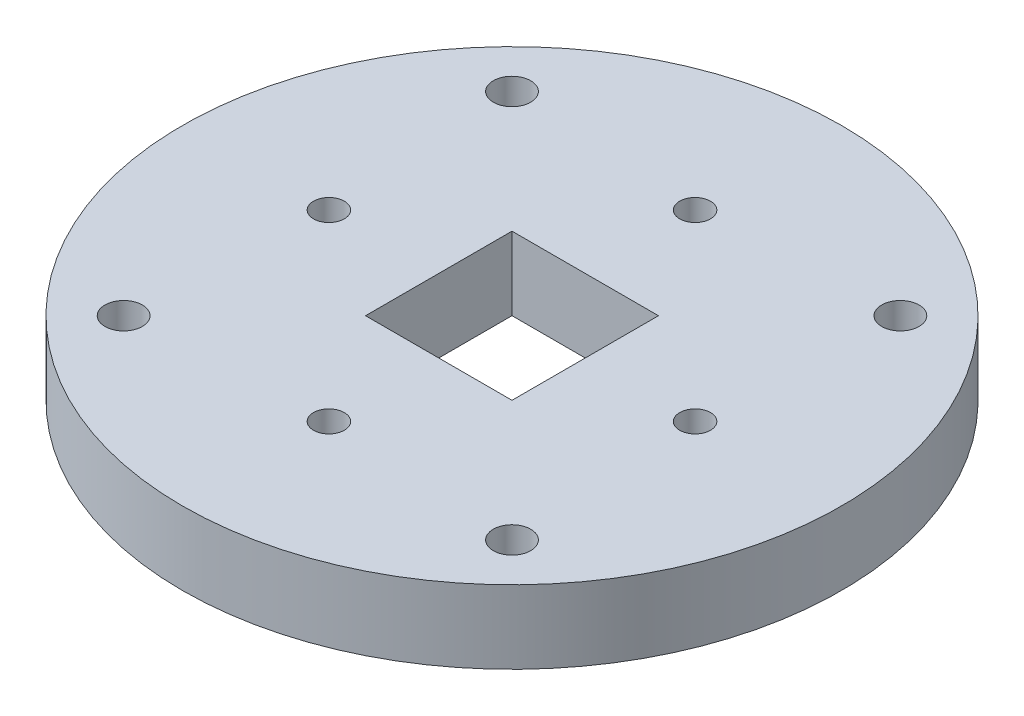
SolidWorks part; units mm, degrees
ref_plane "Front Plane" through (0, 0, 0) normal (0, 0, 1) x (1, 0, 0)
ref_plane "Top Plane" through (0, 0, 0) normal (0, 1, 0) x (1, 0, 0)
ref_plane "Right Plane" through (0, 0, 0) normal (1, 0, 0) x (0, 0, -1)
sketch "Sketch1" plane through (0, 0, 0) normal (0, 1, 0) x (1, 0, 0)
  circle A0 centre (0, 0) radius 45
  dimension "D1" = 90
extrude "Boss-Extrude1" add sketch "Sketch1" along normal blind 10
sketch "Sketch3" plane through (0, 10, 0) normal (0, 1, 0) x (1, 0, 0)
  line L0 (0, -1000) -> (0, 49000) construction
  circle A0 centre (0, 25) radius 2.1
  dimension "D1" = 4.2
  dimension "D2" = 25
extrude "Cut-Extrude2" cut sketch "Sketch3" against normal through all
pattern_circular "CirPattern1" count 4 over 360 about axis through (0, 0, 0) along (0, 1, 0) of "Cut-Extrude2"
sketch "Sketch4" plane through (0, 10, 0) normal (0, 1, 0) x (1, 0, 0)
  line L1 (-10, -10) -> (10, -10)
  line L2 (-10, -10) -> (-10, 10)
  line L3 (-10, 10) -> (10, 10)
  line L4 (10, -10) -> (10, 10)
  line L5 (-10, -10) -> (10, 10) construction
  line L6 (-10, 10) -> (10, -10) construction
  point P0 (0, 0)
  dimension "D1" = 20
  dimension "D2" = 20
extrude "Cut-Extrude3" cut sketch "Sketch4" against normal blind 10
sketch "Sketch6" plane through (0, 10, 0) normal (0, 1, 0) x (1, 0, 0)
  line L0 (-707.1068, -707.1068) -> (34648.2323, 34648.2323) construction
  line L1 (-707.1068, 707.1068) -> (34648.2323, -34648.2323) construction
  line L2 (-1000, 0) -> (49000, 0) construction
  circle A0 centre (0, 0) radius 37.5 construction
  circle A1 centre (-26.5165, 26.5165) radius 2.55
  circle A2 centre (26.5165, 26.5165) radius 2.55
  circle A3 centre (26.5165, -26.5165) radius 2.55
  circle A4 centre (-26.5165, -26.5165) radius 2.55
  circle A5 centre (0, 0) radius 45 construction
  dimension "D1" = 7.5
  dimension "D2" = 5.1
  dimension "D3" = 5.1
  dimension "D4" = 5.1
  dimension "D5" = 5.1
  dimension "D6" = 45
  dimension "D7" = 45
extrude "Cut-Extrude4" cut sketch "Sketch6" against normal through all
